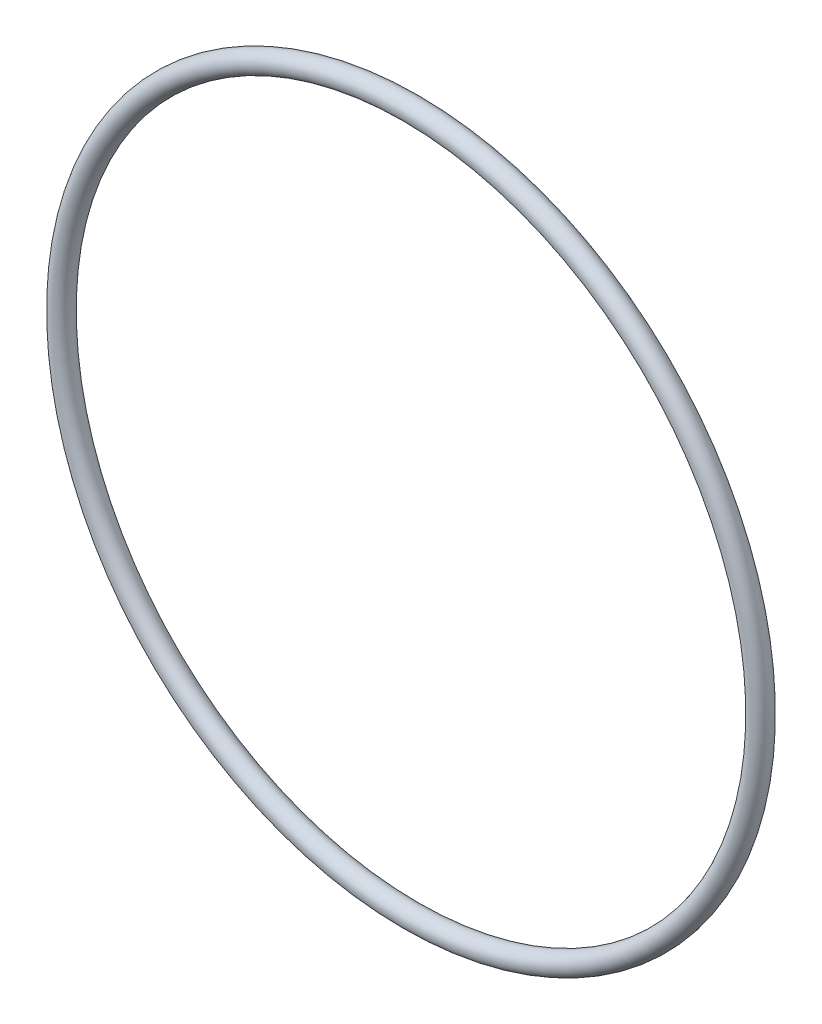
SolidWorks part; units mm, degrees
ref_plane "Front Plane" through (0, 0, 0) normal (0, 0, 1) x (1, 0, 0)
ref_plane "Top Plane" through (0, 0, 0) normal (0, 1, 0) x (1, 0, 0)
ref_plane "Right Plane" through (0, 0, 0) normal (1, 0, 0) x (0, 0, -1)
sketch "Sketch1" plane through (0, 0, 0) normal (0, 0, 1) x (1, 0, 0)
  circle A0 centre (0, 0) radius 50.75
  dimension "D1" = 101.5
sketch "Sketch2" plane through (0, 0, 0) normal (1, 0, 0) x (0, 0, -1)
  line L0 (0, 50.75) -> (0, -50.75) construction
  circle A0 centre (0, 50) radius 1.5
  dimension "D1" = 3
sweep "Sweep1" add profiles "Sketch2" path "Sketch1"
